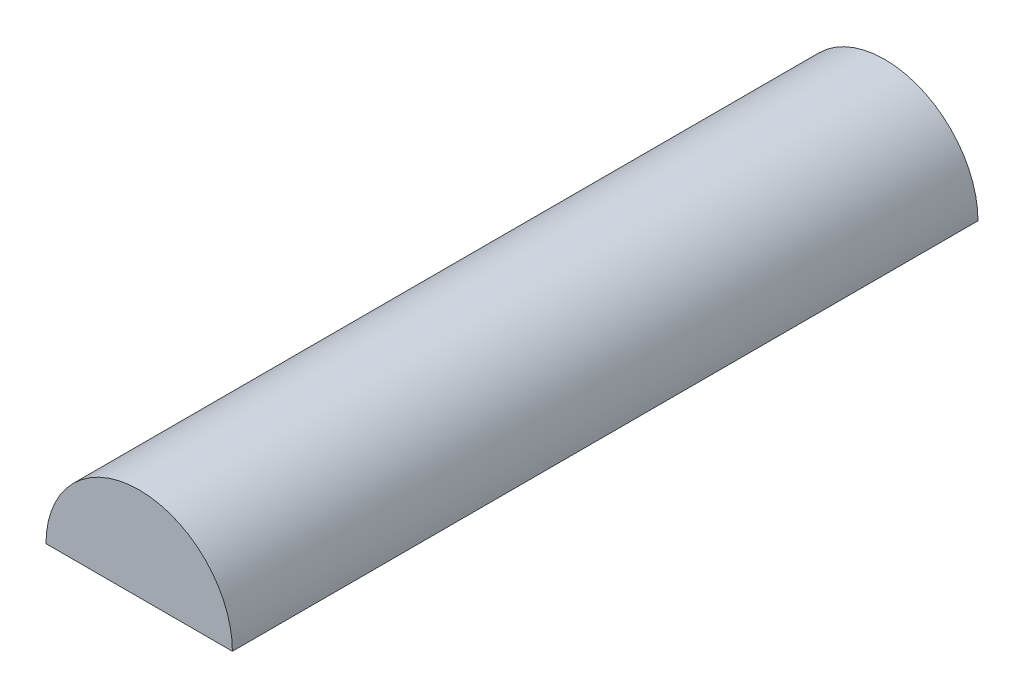
SolidWorks part; units mm, degrees
ref_plane "Спереди" through (0, 0, 0) normal (0, 0, 1) x (1, 0, 0)
ref_plane "Сверху" through (0, 0, 0) normal (0, 1, 0) x (1, 0, 0)
ref_plane "Справа" through (0, 0, 0) normal (1, 0, 0) x (0, 0, -1)
sketch "Эскиз1" plane through (0, 0, 0) normal (0, 0, 1) x (1, 0, 0)
  line L0 (0, 0) -> (25, 0)
  arc A0 (0, 0) -> (25, 0) centre (12.5, 0) cw
  dimension "D1" = 25
extrude "Бобышка-Вытянуть1" add sketch "Эскиз1" along normal blind 100 contours A0 L0
